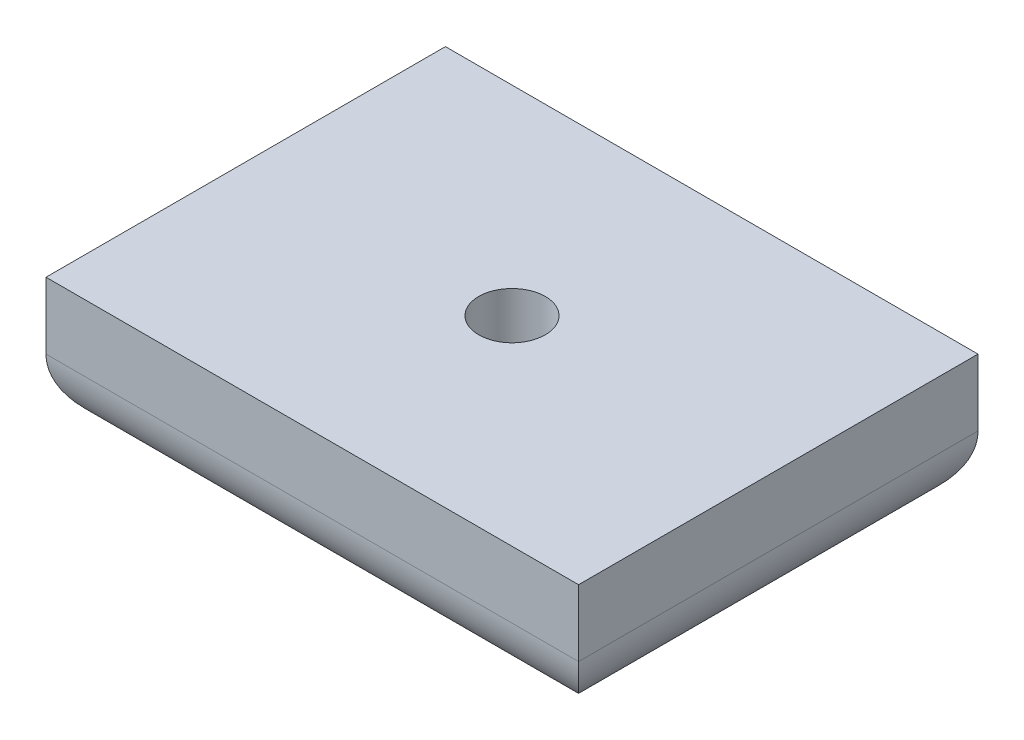
SolidWorks part; units mm, degrees
ref_plane "Plan de face" through (0, 0, 0) normal (0, 0, 1) x (1, 0, 0)
ref_plane "Plan de dessus" through (0, 0, 0) normal (0, 1, 0) x (1, 0, 0)
ref_plane "Plan de droite" through (0, 0, 0) normal (1, 0, 0) x (0, 0, -1)
sketch "Esquisse1" plane through (0, 0, 0) normal (0, 1, 0) x (1, 0, 0)
  line L1 (20, 15) -> (-20, 15)
  line L2 (20, 15) -> (20, -15)
  line L3 (20, -15) -> (-20, -15)
  line L4 (-20, 15) -> (-20, -15)
  line L5 (20, 15) -> (-20, -15) construction
  line L6 (20, -15) -> (-20, 15) construction
  circle A0 centre (0, 0) radius 2.5
  point P0 (0, 0)
  dimension "D3" = 5
  dimension "D1" = 30
  dimension "D2" = 40
extrude "BASE" add sketch "Esquisse1" along normal blind 10
fillet "EXT" radius 5 4 edges at (-20, 0, 0) (0, 0, -15) (20, 0, 0) (0, 0, 15)
sketch "Esquisse2" plane through (0, 0, 0) normal (0, -1, 0) x (-1, 0, 0)
  circle A0 centre (0, 0) radius 4
  dimension "D1" = 8
extrude "ACCES VIS" cut sketch "Esquisse2" against normal blind 5
